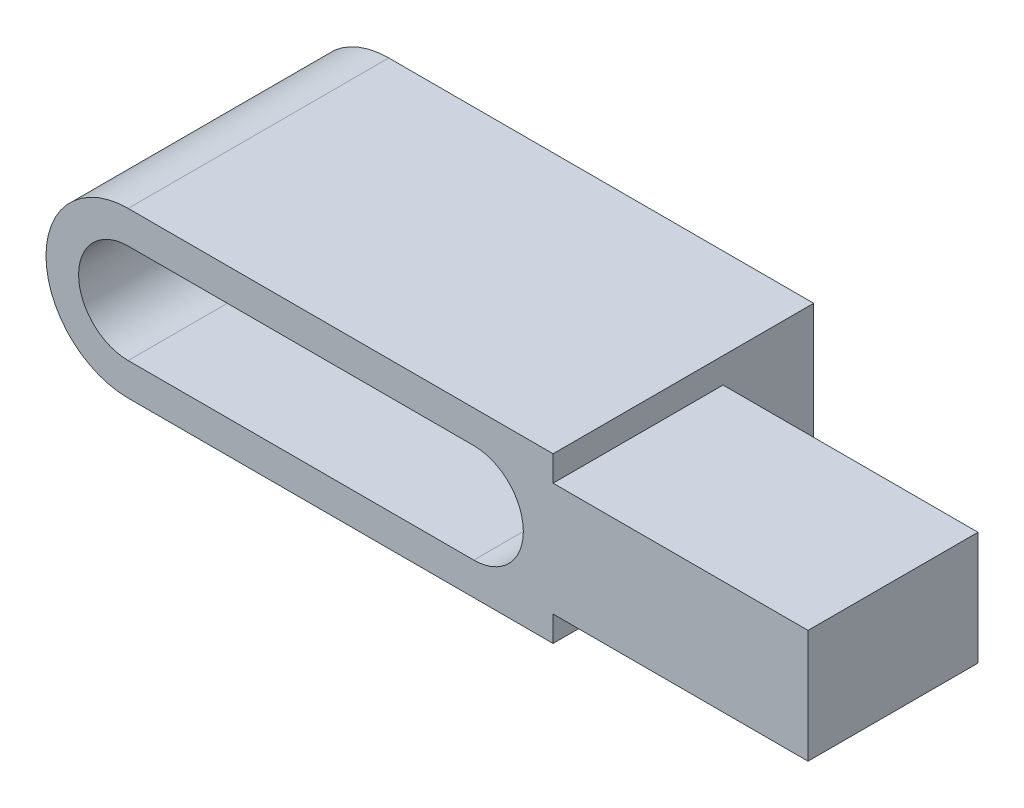
SolidWorks part; units mm, degrees
ref_plane "Спереди" through (0, 0, 0) normal (0, 0, 1) x (1, 0, 0)
ref_plane "Сверху" through (0, 0, 0) normal (0, 1, 0) x (1, 0, 0)
ref_plane "Справа" through (0, 0, 0) normal (1, 0, 0) x (0, 0, -1)
sketch "Эскиз1" plane through (0, 0, 0) normal (0, 0, 1) x (1, 0, 0)
  line L0 (0, 2.9) -> (15, 2.9)
  line L1 (15, 2.9) -> (15, -2.9)
  line L2 (15, -2.9) -> (0, -2.9)
  arc A0 (0, 2.9) -> (0, -2.9) centre (0, 0) ccw
  dimension "D1" = 5.8
  dimension "D2" = 15
extrude "Бобышка-Вытянуть1" add sketch "Эскиз1" along normal blind 3.2
sketch "Эскиз2" plane through (0, 0, 3.2) normal (0, 0, 1) x (1, 0, 0)
  line L0 (24, 2) -> (24, -2)
  line L1 (15, -2.9) -> (15, -2)
  line L2 (15, -2.9) -> (15, 2.9) construction
  line L3 (0, -2.9) -> (15, -2.9)
  line L4 (15, -2.9) -> (15, 2.9)
  line L5 (15, 2.9) -> (0, 2.9)
  line L6 (0, -2.9) -> (15, -2.9)
  line L8 (15, 2.9) -> (0, 2.9)
  line L9 (15, -2) -> (24, -2)
  line L10 (15, 2.9) -> (15, 2)
  line L11 (15, 2) -> (24, 2)
  arc A1 (0, 2.9) -> (0, -2.9) centre (0, 0) ccw
  arc A2 (0, 2.9) -> (0, -2.9) centre (0, 0) ccw
  dimension "D2" = 24
  dimension "D3" = 4
  dimension "D4" = 9
  dimension "D1" = 0
extrude "Бобышка-Вытянуть2" add sketch "Эскиз2" along normal blind 6
sketch "Эскиз3" plane through (0, 0, 9.2) normal (0, 0, 1) x (1, 0, 0)
  line L0 (15, -2.9) -> (15, 2.9) construction
  line L1 (0, 1.75) -> (12.2, 1.75)
  line L2 (12.2, -1.75) -> (0, -1.75)
  arc A0 (0, 1.75) -> (0, -1.75) centre (0, 0) ccw
  arc A1 (12.2, -1.75) -> (12.2, 1.75) centre (12.2, 0) ccw
  dimension "D1" = 3.5
  dimension "D2" = 3.5
  dimension "D3" = 2.8
extrude "Вырез-Вытянуть1" cut sketch "Эскиз3" against normal through all
